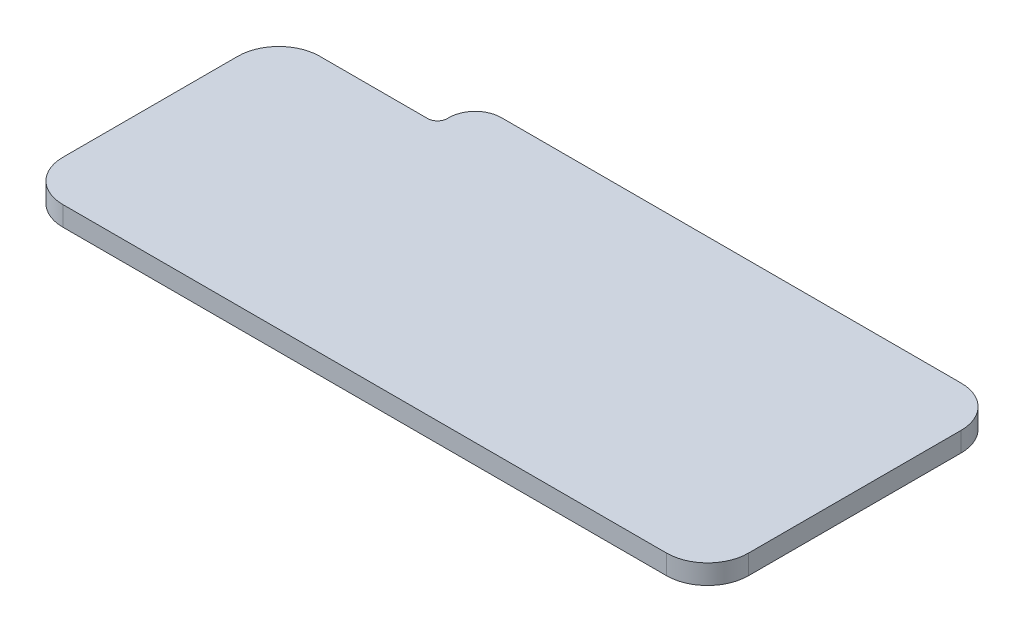
SolidWorks part; units mm, degrees
ref_plane "Спереди" through (0, 0, 0) normal (0, 0, 1) x (1, 0, 0)
ref_plane "Сверху" through (0, 0, 0) normal (0, 1, 0) x (1, 0, 0)
ref_plane "Справа" through (0, 0, 0) normal (1, 0, 0) x (0, 0, -1)
sketch "Эскиз1" plane through (0, 0, 0) normal (0, 1, 0) x (1, 0, 0)
  line L1 (0, 0) -> (297, 0)
  line L2 (0, 162.982) -> (0, 164)
  line L3 (16, 180) -> (297, 180)
  line L4 (322, 25) -> (322, 155)
  line L5 (0, 0) -> (-72, 0)
  line L7 (-6, 156.982) -> (-72, 156.982)
  line L8 (-97, 25) -> (-97, 131.982)
  arc A0 (0, 164) -> (16, 180) centre (16, 164) cw
  arc A1 (0, 162.982) -> (-6, 156.982) centre (-6, 162.982) cw
  arc A2 (297, 180) -> (322, 155) centre (297, 155) cw
  arc A3 (297, 0) -> (322, 25) centre (297, 25) ccw
  arc A4 (-72, 0) -> (-97, 25) centre (-72, 25) cw
  arc A5 (-72, 156.982) -> (-97, 131.982) centre (-72, 131.982) ccw
  point P10 (0, 180)
  point P13 (0, 156.982)
  point P16 (322, 180)
  point P19 (322, 0)
  point P22 (-97, 0)
  point P25 (-97, 156.982)
  dimension "D5" = 16
  dimension "D6" = 6
  dimension "D7" = 25
  dimension "D1" = 322
  dimension "D2" = 180
  dimension "D3" = 97
  dimension "D4" = 156.982
extrude "Бобышка-Вытянуть1" add sketch "Эскиз1" along normal blind 12
